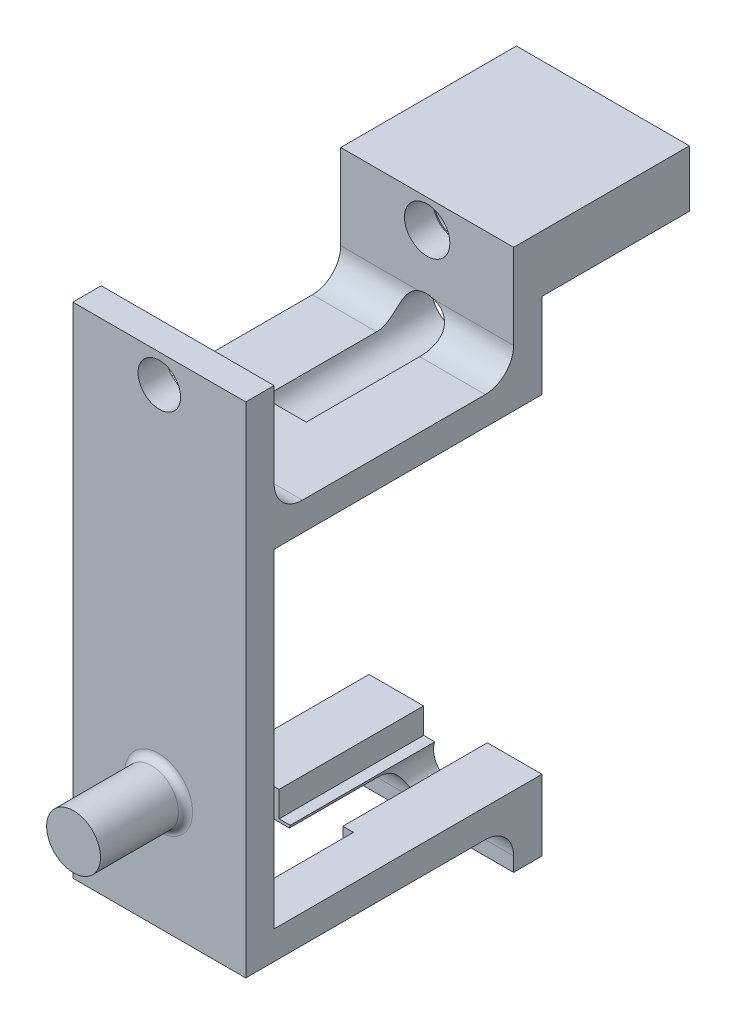
SolidWorks part; units mm, degrees
ref_plane "Front Plane" through (0, 0, 0) normal (0, 0, 1) x (1, 0, 0)
ref_plane "Top Plane" through (0, 0, 0) normal (0, 1, 0) x (1, 0, 0)
ref_plane "Right Plane" through (0, 0, 0) normal (1, 0, 0) x (0, 0, -1)
sketch "Sketch1" plane through (0, 0, 0) normal (1, 0, 0) x (0, 0, -1)
  line L0 (0, 16.6) -> (0, 11.6)
  line L1 (0, 11.6) -> (-18.9, 11.6)
  line L2 (-18.9, 11.6) -> (-18.9, -11.6)
  line L3 (-18.9, -11.6) -> (0, -11.6)
  line L4 (0, -11.6) -> (0, -16.6)
  point P3 (-18.9, 0)
  dimension "D1" = 5
  dimension "D2" = 5
  dimension "D3" = 23.2
  dimension "D4" = 18.9
extrude "Extrude-Thin1" add sketch "Sketch1" along normal blind 12.2 thin
sketch "Sketch2" plane through (0, 0, 18.9) normal (0, 0, -1) x (-1, 0, 0)
  line L0 (0, 11.6) -> (0, -11.6) construction
  line L1 (-12.2, 11.6) -> (0, 11.6) construction
  circle A0 centre (-6.05, -5.15) radius 1.3
  dimension "D1" = 2.6
  dimension "D2" = 6.05
  dimension "D3" = 16.75
extrude "Cut-Extrude1" cut sketch "Sketch2" against normal through all
sketch "Sketch3" plane through (12.2, 0, 0) normal (1, 0, 0) x (0, 0, -1)
  line L0 (-20.9, 13.6) -> (-20.9, -13.6) construction
  line L1 (-18.9, 11.6) -> (-20.9, 11.6)
  line L2 (-18.9, 11.6) -> (-18.9, 21.6)
  line L3 (-18.9, 21.6) -> (-20.9, 21.6)
  line L4 (-20.9, 11.6) -> (-20.9, 21.6)
  dimension "D1" = 10
extrude "Boss-Extrude1" add sketch "Sketch3" against normal up to surface (12.2 mm away) up to face at (0, 0, 7.3)
fillet "Fillet1" radius 2 3 edges at (6.1, -13.6, 2) (6.1, 13.6, 2) (6.1, 13.6, 18.9)
sketch "Sketch4" plane through (0, 0, 18.9) normal (0, 0, -1) x (-1, 0, 0)
  line L0 (0, 21.6) -> (-12.2, 21.6) construction
  circle A0 centre (-6.1, 19.6) radius 1.5
  point P4 (-6.1, 21.6)
  dimension "D1" = 3
  dimension "D2" = 2
extrude "Cut-Extrude2" cut sketch "Sketch4" against normal through all
sketch "Sketch5" plane through (0, 16.6, 0) normal (0, 1, 0) x (1, 0, 0)
  line L0 (0, -2) -> (0, 0) construction
  line L1 (0, 0) -> (12.2, 0)
  line L2 (0, 0) -> (0, -2)
  line L3 (0, -2) -> (12.2, -2)
  line L4 (12.2, 0) -> (12.2, -2)
  line L5 (12.2, -2) -> (12.2, 0) construction
  line L6 (12.2, -2) -> (0, -2) construction
  line L7 (12.2, 0) -> (0, 0) construction
  dimension "D1" = 2
extrude "Boss-Extrude2" add sketch "Sketch5" along normal blind 5
sketch "Sketch8" plane through (0, 0, 2) normal (0, 0, 1) x (1, 0, 0)
  line L0 (0, 21.6) -> (0, 15.6) construction
  line L1 (0, 15.6) -> (12.2, 15.6) construction
  circle A0 centre (6.1, 19.6) radius 1.6
  dimension "D1" = 3.2
  dimension "D2" = 6.1
  dimension "D3" = 4
extrude "Cut-Extrude4" cut sketch "Sketch8" against normal blind 3
sketch "Sketch9" plane through (0, 0, 0) normal (0, 0, -1) x (-1, 0, 0)
  line L0 (0, 21.6) -> (0, 11.6) construction
  line L1 (0, 21.6) -> (-12.2, 21.6)
  line L2 (0, 21.6) -> (0, 17.6)
  line L3 (0, 17.6) -> (-12.2, 17.6)
  line L4 (-12.2, 21.6) -> (-12.2, 17.6)
  line L5 (-12.2, 21.6) -> (0, 21.6) construction
  line L6 (-12.2, 21.6) -> (-12.2, 11.6) construction
  circle A0 centre (-6.1, 19.6) radius 1.5
  dimension "D2" = 3
  dimension "D1" = 4
  dimension "D3" = 2
  dimension "D4" = 6.1
extrude "Boss-Extrude3" add sketch "Sketch9" along normal blind 11.4
sketch "Sketch10" plane through (0, 0, 0) normal (0, 0, -1) x (-1, 0, 0)
  line L0 (0, -11.6) -> (0, -16.6) construction
  line L1 (-12.2, -11.6) -> (0, -11.6) construction
  line L2 (-6.05, 13.9) -> (-6.05, -13.9) construction
  line L3 (-12.2, 11.6) -> (-12.2, -11.6) construction
  circle A0 centre (-6.05, -13.9) radius 1.5
  circle A2 centre (-6.05, 14.1) radius 1.6
  point P10 (-12.2, 0)
  point P11 (-6.05, 0)
  dimension "D1" = 3.2
  dimension "D2" = 3
  dimension "D3" = 6.05
  dimension "D4" = 6.05
  dimension "D5" = 25.5
  dimension "D6" = 6.05
  dimension "D7" = 25.7
extrude "Cut-Extrude5" cut sketch "Sketch10" against normal blind 12
sketch "Sketch12" plane through (0, 0, 18.9) normal (0, 0, -1) x (-1, 0, 0)
  line L0 (0, 11.6) -> (0, -11.6) construction
  line L1 (-12.2, 11.6) -> (0, 11.6) construction
  circle A1 centre (-6.1, 19.6) radius 2 construction
  circle A2 centre (-6.05, -5.35) radius 1.9
  dimension "D1" = 3.8
  dimension "D2" = 4
  dimension "D3" = 6.05
  dimension "D4" = 16.95
extrude "Boss-Extrude5" add sketch "Sketch12" against normal blind 8
sketch "Sketch13" plane through (12.2, 0, 0) normal (1, 0, 0) x (0, 0, -1)
  line L0 (11.4, 17.6) -> (0, 17.6) construction
  line L1 (11.4, 21.6) -> (10.4, 21.6)
  line L2 (11.4, 21.6) -> (11.4, 17.6)
  line L3 (11.4, 17.6) -> (10.4, 17.6)
  line L4 (10.4, 21.6) -> (10.4, 17.6)
  dimension "D1" = 1
extrude "Cut-Extrude6" cut sketch "Sketch13" against normal through all
fillet "Fillet4" radius 0.5 1 edges at (6.05, -3.45, 20.9)
sketch "Sketch14" plane through (0, 0, 0) normal (0, 0, -1) x (-1, 0, 0)
  line L0 (-12.2, -11.6) -> (0, -11.6) construction
  line L1 (-8.35, -11.6) -> (-3.85, -11.6)
  line L2 (-8.35, -11.6) -> (-8.35, -13.4)
  line L3 (-8.35, -13.4) -> (-3.85, -13.4)
  line L4 (-3.85, -11.6) -> (-3.85, -13.4)
  point P6 (-6.1, -11.6)
  point P7 (-6.1, -11.6)
  dimension "D1" = 4.5
  dimension "D2" = 1.8
extrude "Cut-Extrude7" cut sketch "Sketch14" against normal up to surface (18.9 mm away) up to face at (6.1, 0, 18.9)
sketch "Sketch15" plane through (0, -13.6, 0) normal (0, -1, 0) x (1, 0, 0)
  line L0 (12.2, 20.9) -> (0, 20.9) construction
  line L1 (3.1, 10.2) -> (9.1, 10.2)
  line L2 (3.1, 10.2) -> (3.1, 18.4)
  line L3 (3.1, 18.4) -> (9.1, 18.4)
  line L4 (9.1, 10.2) -> (9.1, 18.4)
  point P6 (6.1, 20.9)
  point P7 (6.1, 18.4)
  dimension "D1" = 6
  dimension "D2" = 8.2
  dimension "D3" = 2.5
extrude "Cut-Extrude8" cut sketch "Sketch15" against normal up to surface (2 mm away) up to face at (1.925, -11.6, 9.45)
